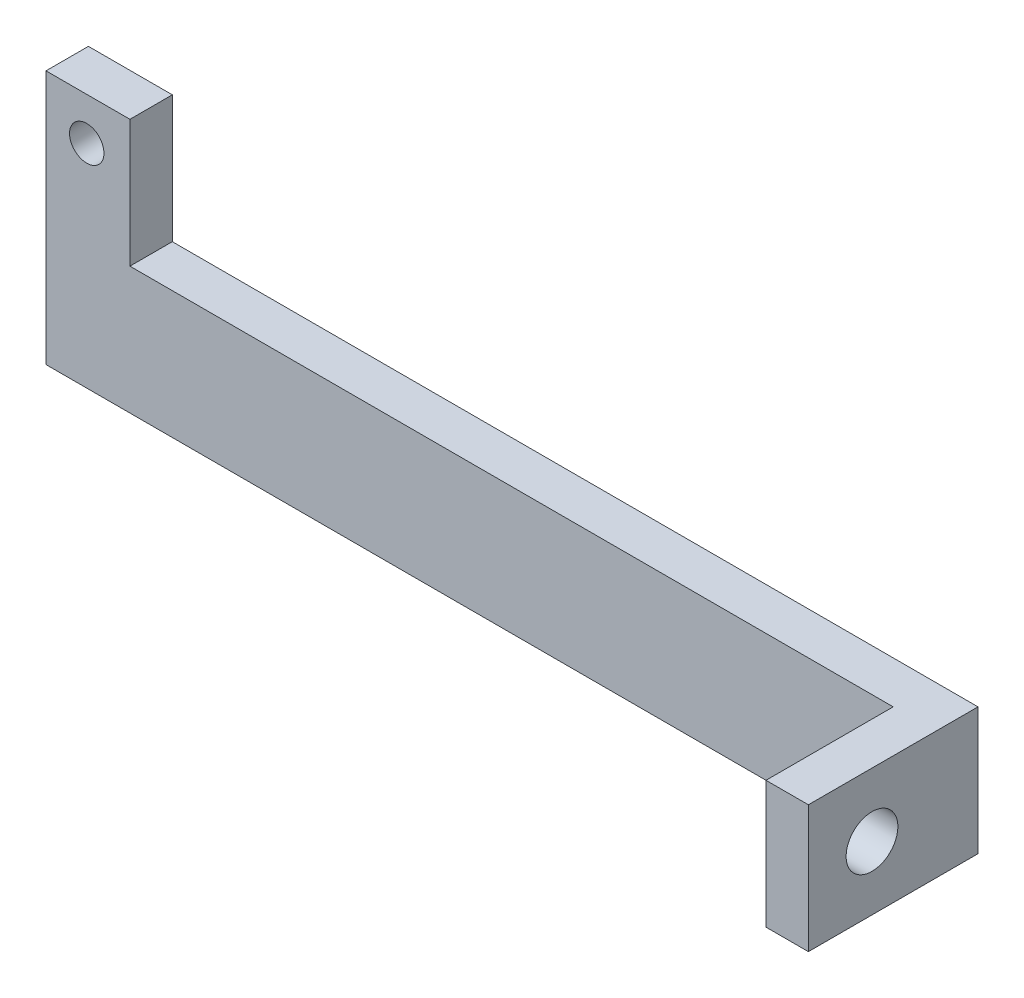
SolidWorks part; units mm, degrees
ref_plane "Front Plane" through (0, 0, 0) normal (0, 0, 1) x (1, 0, 0)
ref_plane "Top Plane" through (0, 0, 0) normal (0, 1, 0) x (1, 0, 0)
ref_plane "Right Plane" through (0, 0, 0) normal (1, 0, 0) x (0, 0, -1)
sketch "Sketch2" plane through (0, 0, 0) normal (0, 0, 1) x (1, 0, 0)
  line L1 (0, 0) -> (48.26, 0)
  line L2 (0, 0) -> (0, 7.62)
  line L3 (0, 7.62) -> (48.26, 7.62)
  line L4 (48.26, 0) -> (48.26, 7.62)
  dimension "D1" = 48.26
  dimension "D2" = 7.62
extrude "Boss-Extrude1" add sketch "Sketch2" along normal blind 2.54
sketch "Sketch3" plane through (0, 0, 0) normal (0, 0, 1) x (1, 0, 0)
  line L1 (0, 0) -> (-5.027, 0)
  line L2 (0, 0) -> (0, 15.24)
  line L3 (0, 15.24) -> (-5.027, 15.24)
  line L4 (-5.027, 0) -> (-5.027, 15.24)
  dimension "D1" = 5.027
  dimension "D2" = 15.24
extrude "Boss-Extrude2" add sketch "Sketch3" along normal blind 2.54
sketch "Sketch4" plane through (0, 0, 2.54) normal (0, 0, 1) x (1, 0, 0)
  line L0 (0, 15.24) -> (-5.027, 15.24) construction
  line L1 (-5.027, 15.24) -> (-5.027, 0) construction
  circle A0 centre (-2.5863, 12.7) radius 1.0305
  dimension "D1" = 2.061
  dimension "D2" = 2.54
  dimension "D3" = 2.4407
extrude "Cut-Extrude1" cut sketch "Sketch4" against normal blind 2.54
ref_plane "Plane1" through (48.26, 0, 0) normal (-1, 0, 0) x (0, 0, 1)
sketch "Sketch5" plane through (48.26, 0, 0) normal (-1, 0, 0) x (0, 0, 1)
  line L0 (2.54, 15.24) -> (2.54, 0) construction
  line L1 (2.54, 7.62) -> (10.16, 7.62)
  line L2 (2.54, 7.62) -> (2.54, 0)
  line L3 (2.54, 0) -> (10.16, 0)
  line L4 (10.16, 7.62) -> (10.16, 0)
  line L5 (2.54, 0) -> (2.54, 7.62) construction
  point P8 (2.54, 3.81)
  point P9 (2.54, 3.81)
  dimension "D1" = 7.62
  dimension "D2" = 7.62
extrude "Boss-Extrude3" add sketch "Sketch5" along normal blind 2.54
sketch "Sketch6" plane through (45.72, 0, 0) normal (-1, 0, 0) x (0, 0, 1)
  line L0 (10.16, 7.62) -> (2.54, 7.62) construction
  line L1 (10.16, 0) -> (10.16, 7.62) construction
  circle A0 centre (6.35, 3.81) radius 1.55
  point P4 (6.35, 7.62)
  point P7 (10.16, 3.81)
  dimension "D1" = 3.1
extrude "Cut-Extrude2" cut sketch "Sketch6" against normal blind 2.54
